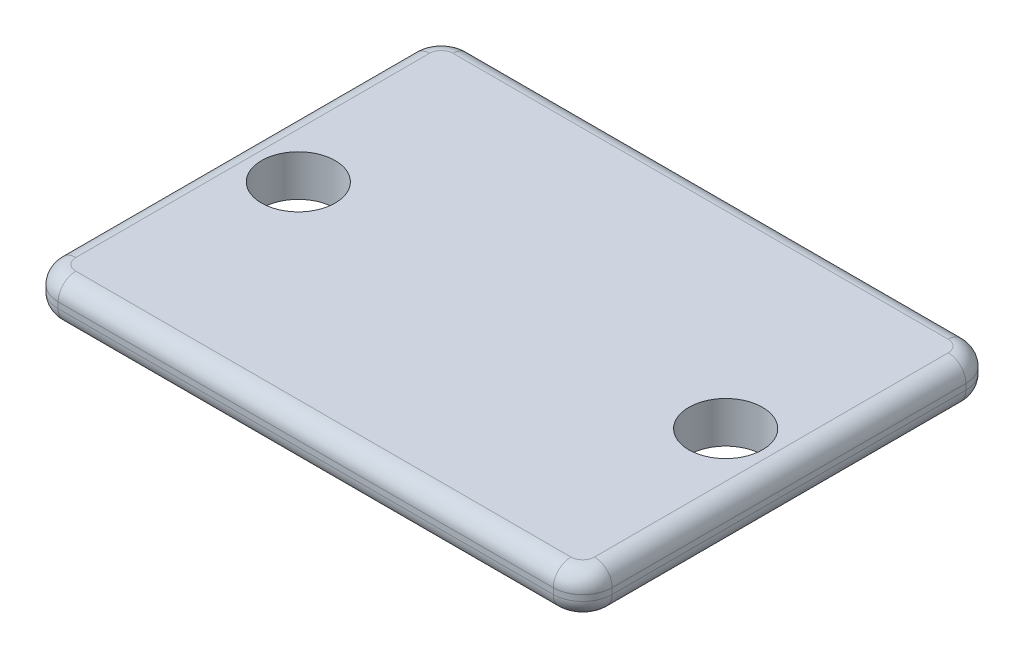
SolidWorks part; units mm, degrees
ref_plane "Front Plane" through (0, 0, 0) normal (0, 0, 1) x (1, 0, 0)
ref_plane "Top Plane" through (0, 0, 0) normal (0, 1, 0) x (1, 0, 0)
ref_plane "Right Plane" through (0, 0, 0) normal (1, 0, 0) x (0, 0, -1)
sketch "Sketch1" plane through (0, 0, 0) normal (0, 1, 0) x (1, 0, 0)
  line L0 (-9.4, 0) -> (9.4, 0) construction
  line L1 (9.4, -7) -> (-9.4, -7)
  line L2 (9.4, -7) -> (9.4, 7)
  line L3 (9.4, 7) -> (-9.4, 7)
  line L4 (-9.4, -7) -> (-9.4, 7)
  line L5 (9.4, -7) -> (-9.4, 7) construction
  line L6 (9.4, 7) -> (-9.4, -7) construction
  line L7 (0, -7) -> (0, 7) construction
  circle A0 centre (-7.25, 0) radius 1.25
  circle A1 centre (7.25, 0) radius 1.25
  point P0 (0, 0)
  dimension "D5" = 2.5
  dimension "D1" = 18.8
  dimension "D2" = 14
  dimension "D3" = 14.5
extrude "Cable Plate Extrude" add sketch "Sketch1" along normal blind 1.4
fillet "Fillet2" radius 1 4 edges at (-9.4, 0.7, 7) (9.4, 0.7, 7) (9.4, 0.7, -7) (-9.4, 0.7, -7)
fillet "Fillet1" radius 0.6 16 edges at (0, 0, 7) (0, 1.4, 7) (9.4, 0, 0) (9.4, 1.4, 0) (0, 0, -7) (-9.4, 0, 0) (0, 1.4, -7) (-9.4, 1.4, 0) (-9.1071, 0, -6.7071) (9.1071, 0, -6.7071) (9.1071, 0, 6.7071) (-9.1071, 0, 6.7071) (-9.1071, 1.4, -6.7071) (9.1071, 1.4, -6.7071) (9.1071, 1.4, 6.7071) (-9.1071, 1.4, 6.7071)
equation "\"PLA_shrink\"=0.3mm"
equation "\"fit_sliding\"=0.5mm"
equation "\"fit_snap\"=0.3mm"
equation "\"fit_tight\"=0.2mm"
equation "\"m2_tap\"= 1.75mm + \"PLA_shrink\""
equation "\"m2_thin_wall\"= 1.9mm + \"PLA_shrink\""
equation "\"m2_standard\"= 2.2mm + \"PLA_shrink\""
equation "\"m2_head\"= 3.45mm + \"PLA_shrink\""
equation "\"m2.5_tap\"= 2.05 + \"PLA_shrink\""
equation "\"m2.5_standard\"= 2.75 + \"PLA_shrink\""
equation "\"m2.5_head\"= 5mm + \"PLA_shrink\""
equation "\"m3_tap\"= 2.5mm + \"PLA_shrink\""
equation "\"m3_standard\"= 3.3mm + \"PLA_shrink\""
equation "\"m3_head\"= 6mm + \"PLA_shrink\""
equation "\"connector_width\"= 9.35mm"
equation "\"wire_width\"= 3.1mm + \"PLA_shrink\""
equation "\"D5@Sketch1\"=\"m2_standard\""
